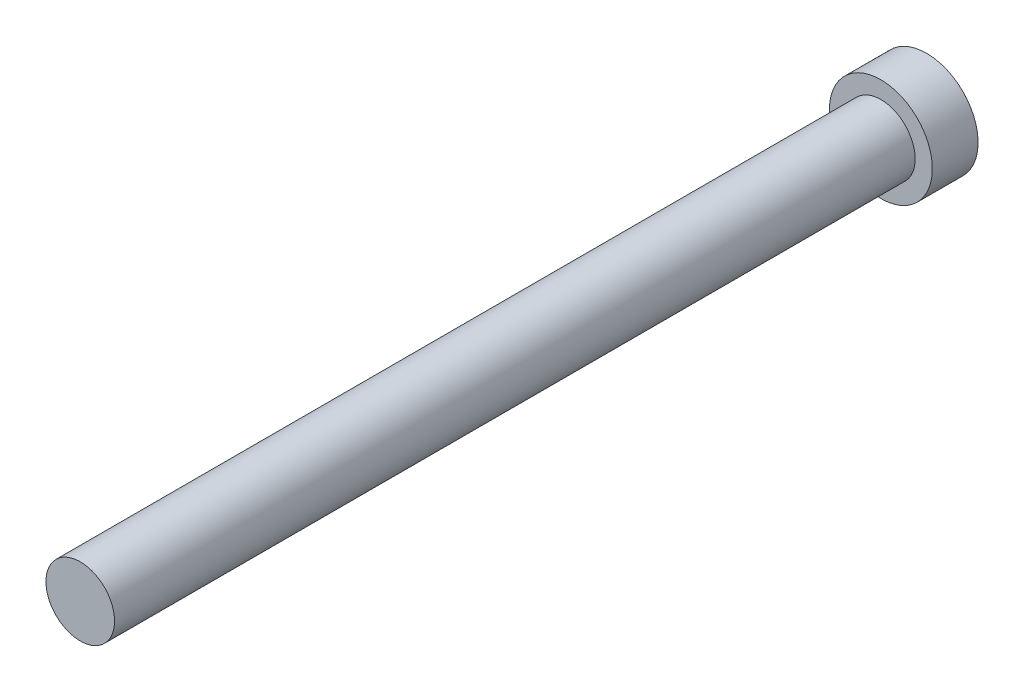
SolidWorks part; units mm, degrees
ref_plane "Front Plane" through (0, 0, 0) normal (0, 0, 1) x (1, 0, 0)
ref_plane "Top Plane" through (0, 0, 0) normal (0, 1, 0) x (1, 0, 0)
ref_plane "Right Plane" through (0, 0, 0) normal (1, 0, 0) x (0, 0, -1)
sketch "Sketch2" plane through (0, 0, 0) normal (0, 0, 1) x (1, 0, 0)
  circle A0 centre (0, 0) radius 1.5
  dimension "D1" = 3
extrude "Boss-Extrude1" add sketch "Sketch2" along normal blind 35
sketch "Sketch3" plane through (0, 0, 0) normal (0, 0, -1) x (-1, 0, 0)
  circle A0 centre (0, 0) radius 2.25
  dimension "D1" = 4.5
extrude "Boss-Extrude2" add sketch "Sketch3" along normal blind 2
